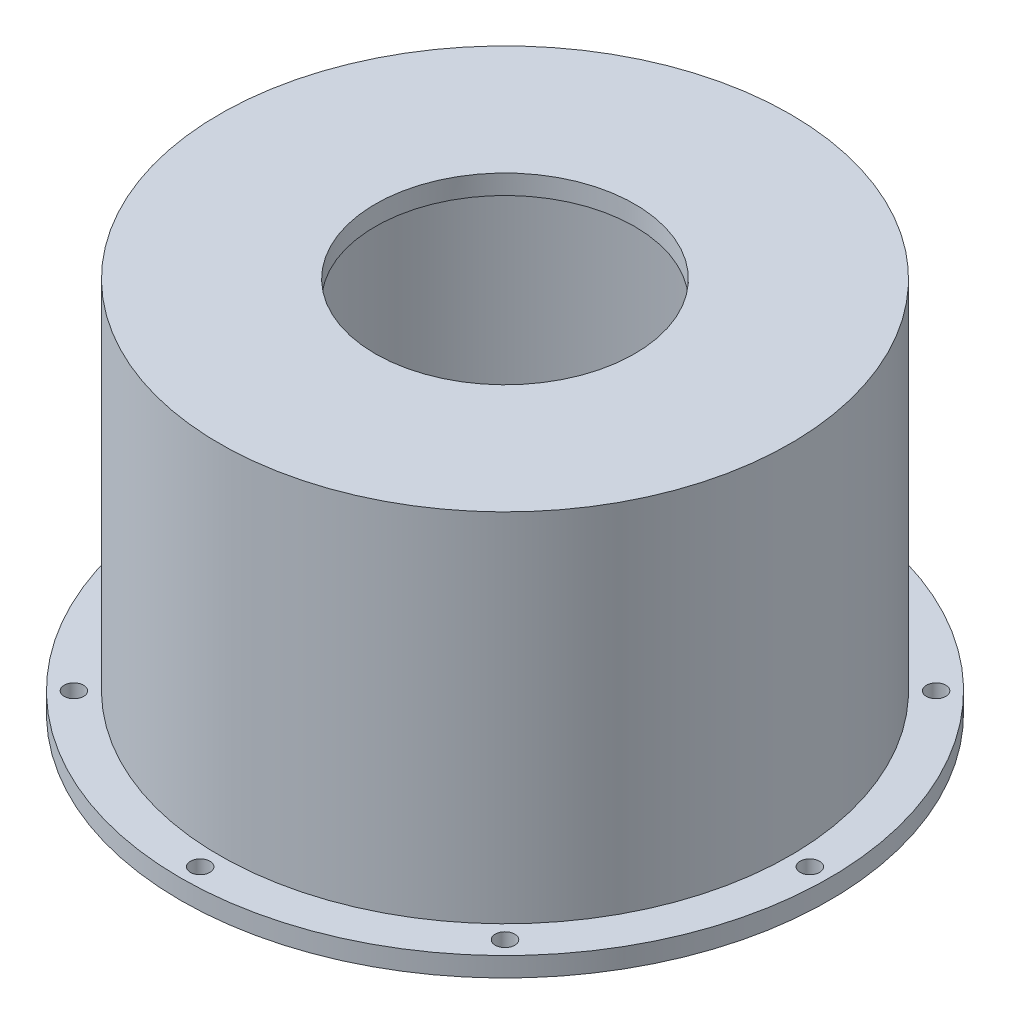
SolidWorks part; units mm, degrees
ref_plane "Front Plane" through (0, 0, 0) normal (0, 0, 1) x (1, 0, 0)
ref_plane "Top Plane" through (0, 0, 0) normal (0, 1, 0) x (1, 0, 0)
ref_plane "Right Plane" through (0, 0, 0) normal (1, 0, 0) x (0, 0, -1)
sketch "Sketch1" plane through (0, 0, 0) normal (0, 0, 1) x (1, 0, 0)
  line L0 (0, 0) -> (0, 18.1259) construction
  line L1 (0, 58) -> (44, 58)
  line L2 (44, 58) -> (44, 3)
  line L3 (44, 3) -> (50, 3)
  line L4 (50, 3) -> (50, 0)
  line L5 (50, 0) -> (41.5, 0)
  line L6 (41.5, 0) -> (41.5, 55)
  line L7 (41.5, 55) -> (0, 55)
  line L8 (0, 55) -> (0, 58)
  point P7 (44, 30.5)
  point P13 (47, 3)
  dimension "D1" = 58
  dimension "D2" = 2.5
  dimension "D3" = 3
  dimension "D4" = 3
  dimension "D5" = 50
  dimension "D6" = 6
revolve "Revolve1" add sketch "Sketch1" angle 360 about L0
sketch "Sketch2" plane through (0, 3, 0) normal (0, 1, 0) x (1, 0, 0)
  line L0 (0, 0) -> (0, -47) construction
  circle A0 centre (0, 0) radius 47 construction
  circle A1 centre (0, -47) radius 1.5
  circle A2 centre (-33.234, -33.234) radius 1.5
  circle A3 centre (-47, 0) radius 1.5
  circle A4 centre (-33.234, 33.234) radius 1.5
  circle A5 centre (0, 47) radius 1.5
  circle A6 centre (33.234, 33.234) radius 1.5
  circle A7 centre (47, 0) radius 1.5
  circle A8 centre (33.234, -33.234) radius 1.5
  dimension "D1" = 94
  dimension "D2" = 3
  dimension "D3" = 8
extrude "Cut-Extrude1" cut sketch "Sketch2" against normal through all
sketch "Sketch3" plane through (0, 58, 0) normal (0, 1, 0) x (1, 0, 0)
  circle A0 centre (0, 0) radius 20
  dimension "D1" = 40
extrude "Cut-Extrude2" cut sketch "Sketch3" against normal through all
